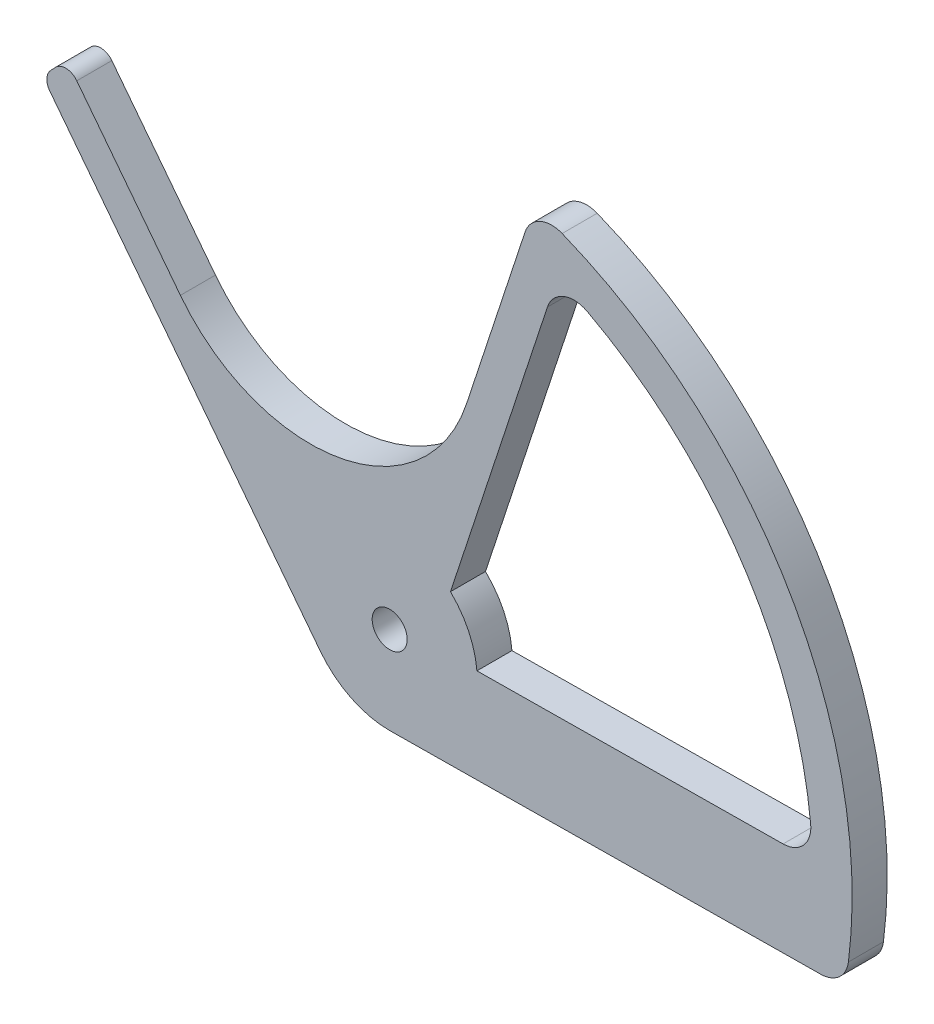
SolidWorks part; units mm, degrees
ref_plane "Front Plane" through (0, 0, 0) normal (0, 0, 1) x (1, 0, 0)
ref_plane "Top Plane" through (0, 0, 0) normal (0, 1, 0) x (1, 0, 0)
ref_plane "Right Plane" through (0, 0, 0) normal (1, 0, 0) x (0, 0, -1)
sketch "Sketch1" plane through (0, 0, 0) normal (0, 0, 1) x (1, 0, 0)
  line L0 (-12.5577, -9.7118) -> (-62.908, 55.393)
  line L1 (-58.4808, 60.0482) -> (-37.9305, 33.4759)
  line L2 (26.1741, 79.6286) -> (13.9364, 42.3983)
  line L3 (30.3981, 70.3954) -> (11.0162, 11.4306)
  line L5 (76.6511, 2.0401) -> (15.8127, 1.4053)
  line L6 (0, -15.875) -> (82.4643, -15.0146)
  circle A2 centre (0, 0) radius 3.175
  arc A3 (-12.5577, -9.7118) -> (0, -15.875) centre (0, 0) ccw
  arc A4 (-58.4808, 60.0482) -> (-62.908, 55.393) centre (0, 0) ccw
  arc A5 (-37.9305, 33.4759) -> (13.9364, 42.3983) centre (-14.3648, 51.701) ccw
  arc A7 (82.4643, -15.0146) -> (26.1741, 79.6286) centre (0, 0) ccw
  arc A8 (76.6511, 2.0401) -> (30.3981, 70.3954) centre (0, 0) ccw
  arc A9 (15.8127, 1.4053) -> (11.0162, 11.4306) centre (0, 0) ccw
  point P1 (1.647, 0)
  dimension "D2" = 6.35
  dimension "D3" = 31.75
  dimension "D5" = 167.64
  dimension "D4" = 6.35
extrude "Boss-Extrude1" add sketch "Sketch1" along normal blind 6.35 contours L6 A7 L2 A5 L1 A4 L0 A3 A2 L5 A9 L3 A8
fillet "Fillet1" radius 5.08 4 edges at (76.6511, 2.0401, 3.175) (30.3981, 70.3954, 3.175) (82.4643, -15.0146, 3.175) (26.1741, 79.6286, 3.175)
fillet "Fillet2" radius 2.54 2 edges at (-58.4808, 60.0482, 3.175) (-62.908, 55.393, 3.175)
